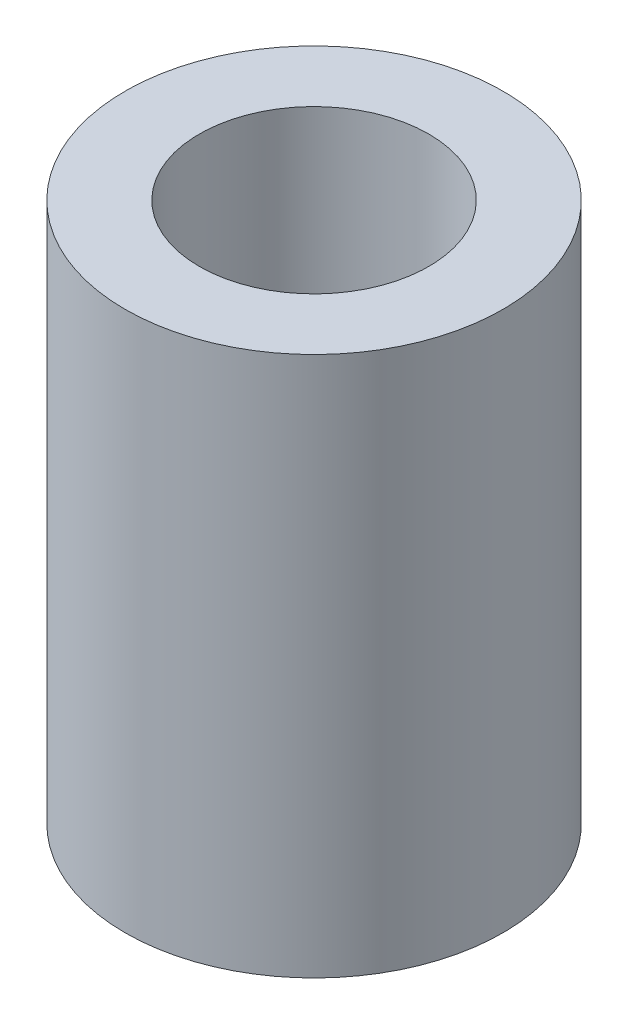
SolidWorks part; units mm, degrees
material "ABS"
ref_plane "Płaszczyzna przednia" through (0, 0, 0) normal (0, 0, 1) x (1, 0, 0)
ref_plane "Płaszczyzna górna" through (0, 0, 0) normal (0, 1, 0) x (1, 0, 0)
ref_plane "Płaszczyzna prawa" through (0, 0, 0) normal (1, 0, 0) x (0, 0, -1)
sketch "Szkic1" plane through (0, 0, 0) normal (0, 1, 0) x (1, 0, 0)
  circle A0 centre (0, 0) radius 4.25
  circle A1 centre (0, 0) radius 7
  dimension "D1" = 8.5
  dimension "D2" = 14
extrude "Dodanie-wyciągnięcie1" add sketch "Szkic1" along normal mid plane 20
